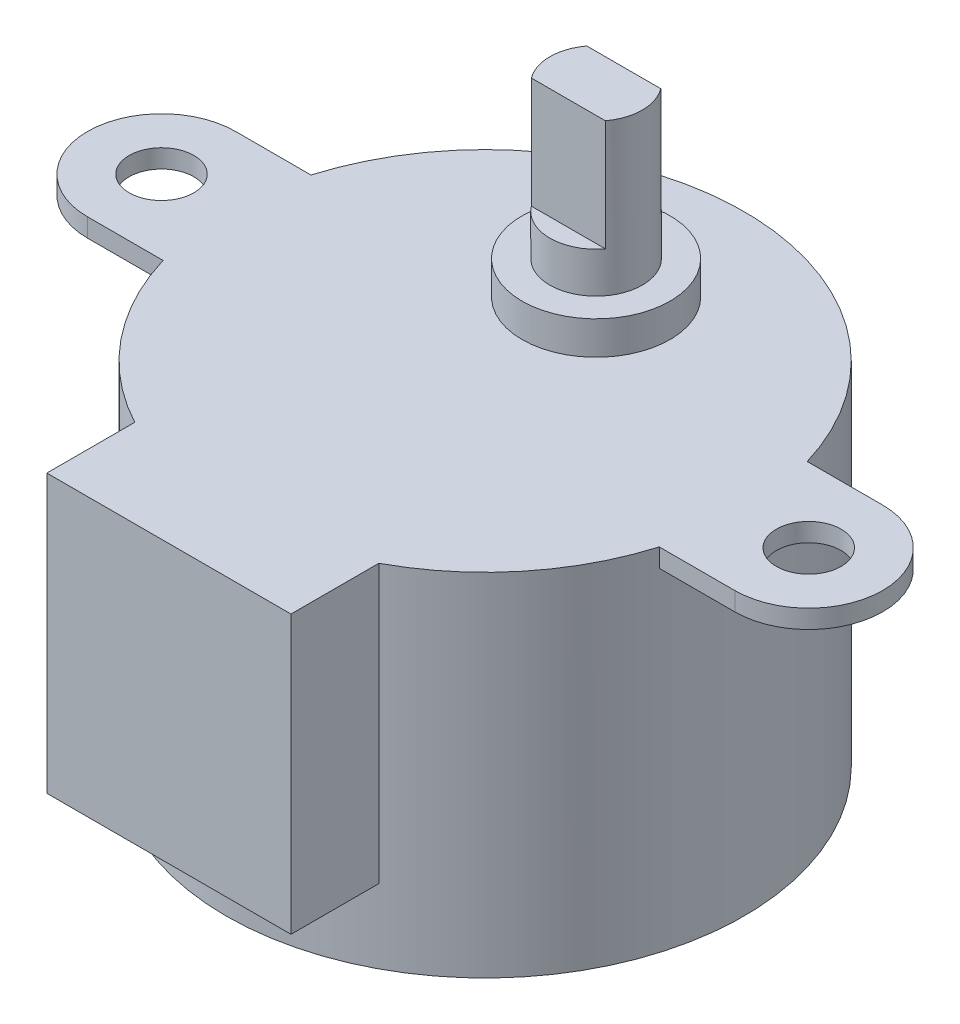
SolidWorks part; units mm, degrees
ref_plane "前视基准面" through (0, 0, 0) normal (0, 0, 1) x (1, 0, 0)
ref_plane "上视基准面" through (0, 0, 0) normal (0, 1, 0) x (1, 0, 0)
ref_plane "右视基准面" through (0, 0, 0) normal (1, 0, 0) x (0, 0, -1)
sketch "草图1" plane through (0, 0, 0) normal (0, 1, 0) x (1, 0, 0)
  circle A0 centre (0, 0) radius 14
  dimension "D1" = 28
extrude "凸台-拉伸1" add sketch "草图1" along normal blind 19
sketch "草图2" plane through (0, 19, 0) normal (0, 1, 0) x (1, 0, 0)
  line L1 (6.6014, -17.1) -> (-6.6014, -17.1)
  line L2 (6.6014, -17.1) -> (6.6014, -10.9)
  line L3 (6.6014, -10.9) -> (-6.6014, -10.9)
  line L4 (-6.6014, -17.1) -> (-6.6014, -10.9)
  line L5 (6.6014, -17.1) -> (-6.6014, -10.9) construction
  line L6 (6.6014, -10.9) -> (-6.6014, -17.1) construction
  circle A0 centre (0, 0) radius 14 construction
  point P0 (0, -14)
  dimension "D1" = 17.1
  dimension "D2" = 0
extrude "凸台-拉伸2" add sketch "草图2" against normal blind 15
sketch "草图3" plane through (0, 19, 0) normal (0, 1, 0) x (1, 0, 0)
  line L0 (17.5, 0) -> (-17.5, 0) construction
  line L1 (17.5, -4) -> (-17.5, -4)
  line L2 (17.5, 4) -> (-17.5, 4)
  arc A0 (17.5, -4) -> (17.5, 4) centre (17.5, 0) ccw
  arc A1 (-17.5, 4) -> (-17.5, -4) centre (-17.5, 0) ccw
  circle A2 centre (-17.5, 0) radius 1.75
  circle A3 centre (17.5, 0) radius 1.75
  point P2 (0, 0)
  dimension "D2" = 4
  dimension "D3" = 3.5
  dimension "D4" = 3.5
  dimension "D1" = 35
extrude "凸台-拉伸3" add sketch "草图3" against normal blind 1
sketch "草图4" plane through (0, 19, 0) normal (0, 1, 0) x (1, 0, 0)
  circle A0 centre (0, 6) radius 4
  dimension "D1" = 8
  dimension "D2" = 6
extrude "凸台-拉伸4" add sketch "草图4" along normal blind 1.8
sketch "草图5" plane through (0, 20.8, 0) normal (0, 1, 0) x (1, 0, 0)
  circle A0 centre (0, 6) radius 2.5
  dimension "D1" = 5
extrude "凸台-拉伸5" add sketch "草图5" along normal blind 8.2
sketch "草图6" plane through (0, 29, 0) normal (0, 1, 0) x (1, 0, 0)
  line L1 (2.5, 7.5) -> (-2.5, 7.5)
  line L2 (2.5, 7.5) -> (2.5, 9.5)
  line L3 (2.5, 9.5) -> (-2.5, 9.5)
  line L4 (-2.5, 7.5) -> (-2.5, 9.5)
  line L5 (2.5, 7.5) -> (-2.5, 9.5) construction
  line L6 (2.5, 9.5) -> (-2.5, 7.5) construction
  line L11 (2.5, 2.5) -> (-2.5, 2.5)
  line L12 (2.5, 2.5) -> (2.5, 4.5)
  line L13 (2.5, 4.5) -> (-2.5, 4.5)
  line L14 (-2.5, 2.5) -> (-2.5, 4.5)
  line L15 (2.5, 2.5) -> (-2.5, 4.5) construction
  line L16 (2.5, 4.5) -> (-2.5, 2.5) construction
  circle A0 centre (0, 6) radius 2.5 construction
  circle A1 centre (0, 6) radius 2.5 construction
  circle A2 centre (0, 6) radius 2.5
  point P0 (0, 8.5)
  point P9 (0, 3.5)
  circle M11 centre (0, 6) radius 2.5
  dimension "D1" = 2
  dimension "D2" = 5
  dimension "D3" = 2
  dimension "D4" = 5
extrude "切除-拉伸1" cut sketch "草图6" against normal blind 6 contours L13 M11 | L1 M11
